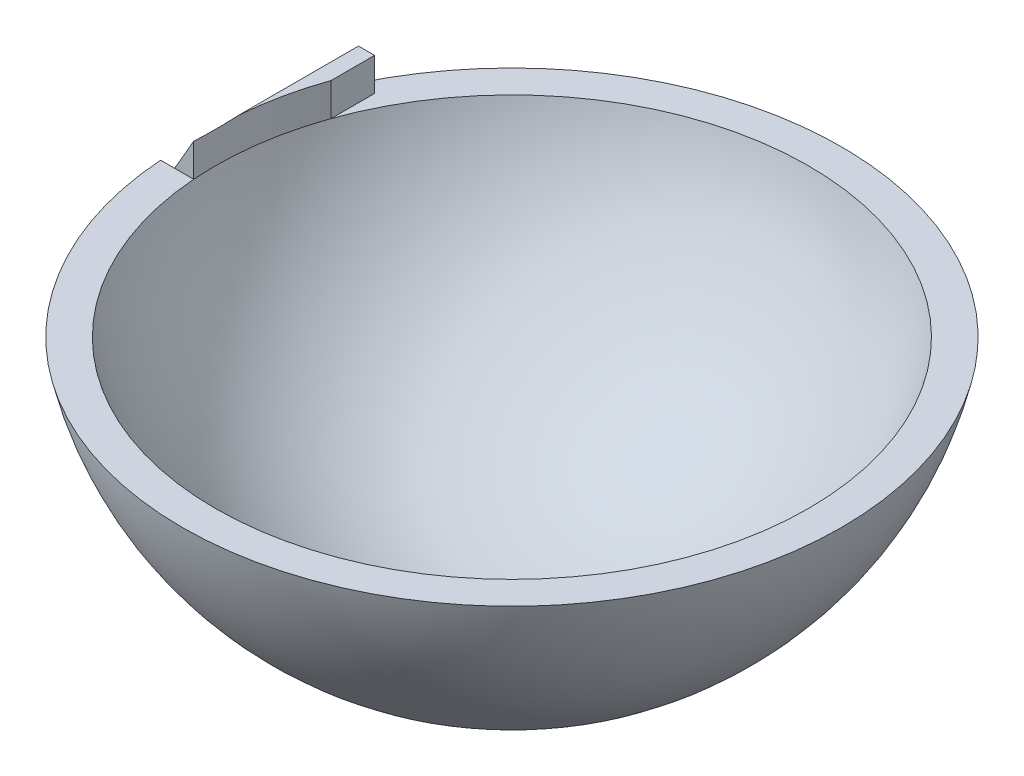
SolidWorks part; units mm, degrees
ref_plane "Front Plane" through (0, 0, 0) normal (0, 0, 1) x (1, 0, 0)
ref_plane "Top Plane" through (0, 0, 0) normal (0, 1, 0) x (1, 0, 0)
ref_plane "Right Plane" through (0, 0, 0) normal (1, 0, 0) x (0, 0, -1)
sketch "Sketch2" plane through (0, 0, 0) normal (0, 0, 1) x (1, 0, 0)
  line L0 (0, 0) -> (63.5, 0)
  line L1 (0, 0) -> (57.15, 0)
  line L2 (0, 0) -> (0, -50.8)
  line L3 (0, 0) -> (0, -44.45)
  line L4 (0, 0) -> (-57.15, 0)
  line L5 (0, 0) -> (-63.5, 0)
  line L6 (0, -50.8) -> (0, -50.9477)
  arc A0 (63.5, 0) -> (-63.5, 0) centre (0, 14.0986) cw
  arc A1 (57.15, 0) -> (-57.15, 0) centre (0, 14.2904) cw
  dimension "D1" = 63.5
  dimension "D2" = 57.15
  dimension "D3" = 50.8
  dimension "D4" = 44.45
  dimension "D5" = 57.15
  dimension "D6" = 63.5
revolve "Revolve1" add sketch "Sketch2" angle 360 about L2
sketch "Sketch5" plane through (0, 0, 0) normal (0, 1, 0) x (1, 0, 0)
  line L0 (0, 19.05) -> (-53.8815, 19.05)
  line L1 (-53.8815, 19.05) -> (-53.8815, 27.432)
  line L3 (-53.8815, 27.432) -> (-63.353, 27.432)
  line L4 (-53.8815, 27.432) -> (-53.8815, -4.318)
  line L5 (-53.8815, -4.318) -> (-63.353, -4.318)
  line L6 (-63.353, 27.432) -> (-63.353, -4.318)
  circle A0 centre (0, 0) radius 19.05 construction
  circle A1 centre (0, 0) radius 19.05 construction
  circle A2 centre (0, 0) radius 57.15 construction
  circle A3 centre (0, 0) radius 63.5 construction
  circle M3 centre (0, 0) radius 63.5
  circle M4 centre (0, 0) radius 57.15
  dimension "D1" = 8.382
  dimension "D2" = 31.75
extrude "Boss-Extrude1" add sketch "Sketch5" along normal blind 6.35 contours L6 L5 L1 L3 M3 M4
sketch "Sketch6" plane through (0, 0, 4.318) normal (0, 0, 1) x (1, 0, 0)
  line L0 (-56.9866, 6.35) -> (-62.6378, -3.438)
  line L1 (-56.9866, 6.35) -> (-56.9866, 0) construction
  line L2 (-63.353, 6.35) -> (-63.353, 0) construction
  line L3 (-56.9866, 6.35) -> (-63.353, 6.35) construction
  line L4 (-63.353, 6.35) -> (-63.353, 0)
  line L5 (-56.9866, 6.35) -> (-63.353, 6.35)
  arc A0 (-63.5, 0) -> (63.5, 0) centre (0, 14.0986) ccw construction
  arc A1 (-63.5, 0) -> (63.5, 0) centre (0, 14.0986) ccw
  line M2 (-63.353, 0) -> (-56.9866, 0)
  line M4 (-56.9866, 6.35) -> (-63.353, 6.35)
  line M5 (-63.353, 6.35) -> (-63.353, 0)
  dimension "D1" = 30
extrude "Cut-Extrude1" cut sketch "Sketch6" against normal blind 33.02 contours L0 M4 M5 M2
sketch "Sketch7" plane through (0, 0, 0) normal (0, 1, 0) x (1, 0, 0)
  line L0 (-60.6528, -4.318) -> (-63.353, -4.318)
  line L1 (-60.6528, 18.8012) -> (-60.6528, -4.318) construction
  line L2 (-60.6528, 18.8012) -> (-60.6528, -4.318)
  arc A0 (-60.6528, 18.8012) -> (-57.269, 27.432) centre (0, 0) ccw construction
  arc A1 (-60.6528, 18.8012) -> (-57.269, 27.432) centre (0, 0) ccw
  line M2 (-60.6528, -4.318) -> (-60.6528, 18.8012)
  arc M3 (-60.6528, 18.8012) -> (-57.269, 27.432) centre (0, 0) ccw
extrude "Cut-Extrude2" cut sketch "Sketch7" against normal blind 10.16 contours L0 M2 M3
